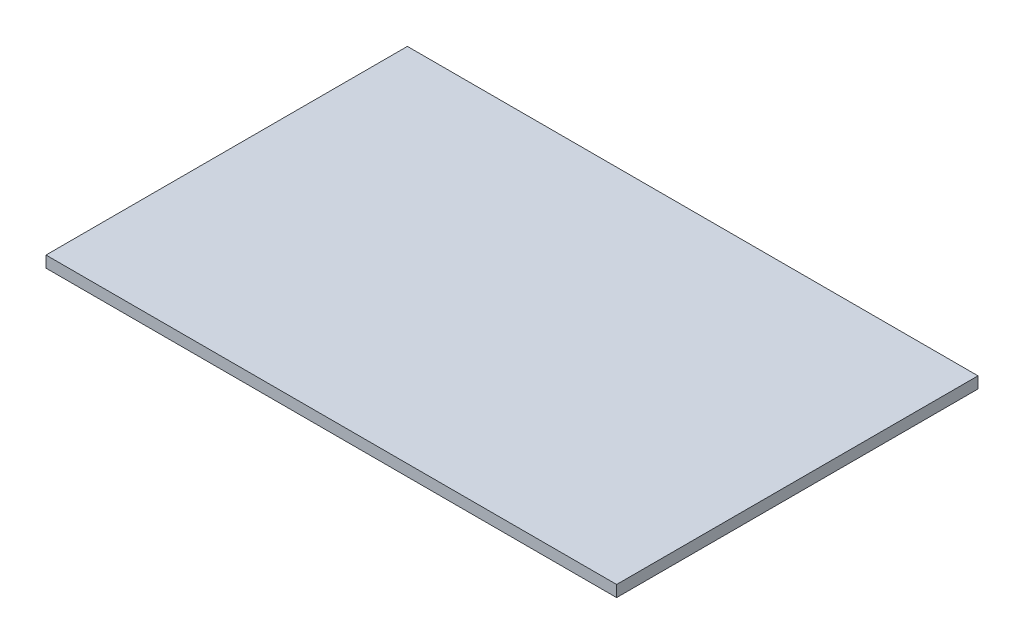
SolidWorks part; units mm, degrees
ref_plane "Front Plane" through (0, 0, 0) normal (0, 0, 1) x (1, 0, 0)
ref_plane "Top Plane" through (0, 0, 0) normal (0, 1, 0) x (1, 0, 0)
ref_plane "Right Plane" through (0, 0, 0) normal (1, 0, 0) x (0, 0, -1)
sketch "Sketch1" plane through (0, 0, 0) normal (0, 1, 0) x (1, 0, 0)
  line L0 (-476.25, 298.45) -> (-476.25, -304.8) construction
  line L1 (-476.25, 298.45) -> (476.25, 298.45) construction
  line L2 (476.25, 298.45) -> (476.25, -304.8) construction
  line L3 (-476.25, -304.8) -> (476.25, -304.8) construction
  line L4 (-476.25, 298.45) -> (-476.25, -304.8)
  line L5 (-476.25, 298.45) -> (476.25, 298.45)
  line L6 (476.25, 298.45) -> (476.25, -304.8)
  line L7 (-476.25, -304.8) -> (476.25, -304.8)
extrude "Boss-Extrude1" add sketch "Sketch1" against normal blind 19.05
